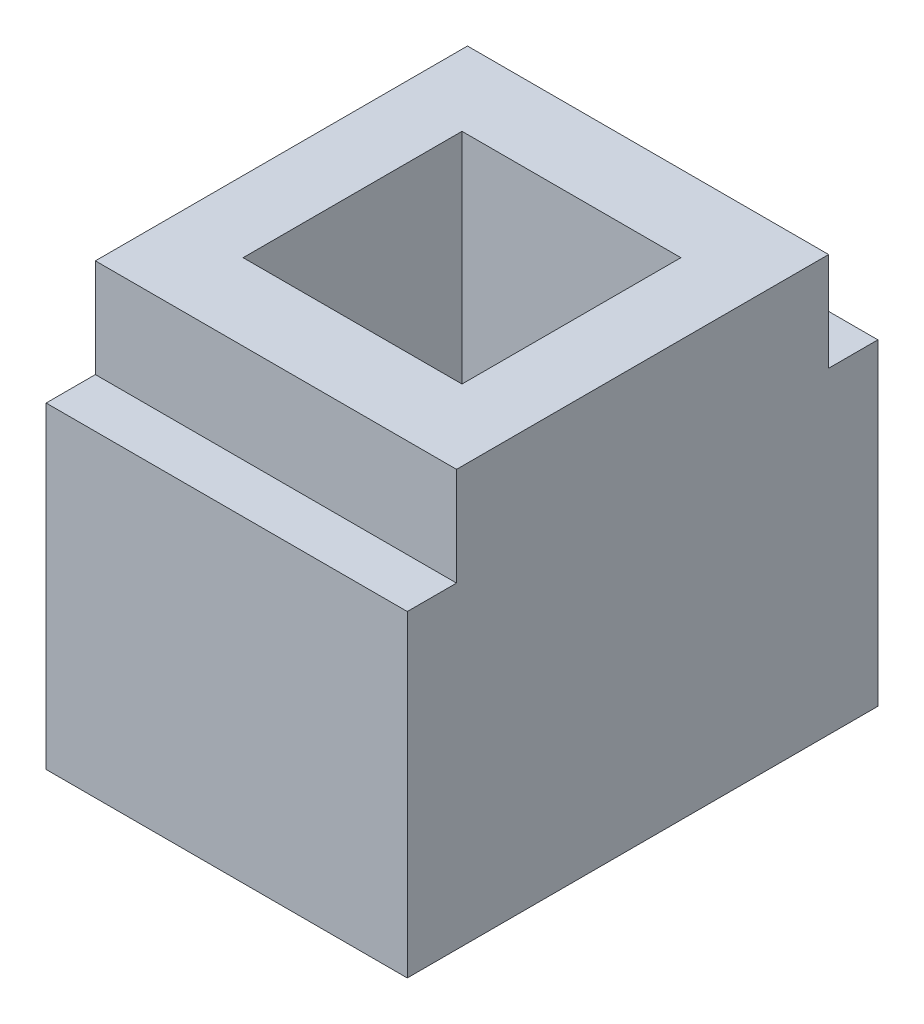
SolidWorks part; units mm, degrees
ref_plane "Alzado" through (0, 0, 0) normal (0, 0, 1) x (1, 0, 0)
ref_plane "Planta" through (0, 0, 0) normal (0, 1, 0) x (1, 0, 0)
ref_plane "Vista lateral" through (0, 0, 0) normal (1, 0, 0) x (0, 0, -1)
sketch "Croquis1" plane through (0, 0, 0) normal (1, 0, 0) x (0, 0, -1)
  line L0 (0, 0) -> (0, 31.7429) construction
  line L1 (-43, 38) -> (43, 38)
  line L2 (-43, 38) -> (-43, -38)
  line L3 (-43, -38) -> (43, -38)
  line L4 (43, 38) -> (43, -38)
  line L5 (-43, 38) -> (43, -38) construction
  line L6 (-43, -38) -> (43, 38) construction
  line L7 (-43, 38) -> (-34, 38)
  line L8 (-43, 38) -> (-43, 20)
  line L9 (-43, 20) -> (-34, 20)
  line L10 (-34, 38) -> (-34, 20)
  line L11 (43, 20) -> (34, 20)
  line L12 (34, 38) -> (34, 20)
  line L13 (43, 38) -> (34, 38)
  line L14 (43, 38) -> (43, 20)
  point P0 (0, 0)
  dimension "D1" = 86
  dimension "D2" = 76
  dimension "D3" = 58
  dimension "D4" = 68
extrude "Saliente-Extruir1" add sketch "Croquis1" along normal mid plane 66 contours L12 L1 L10 L9 L2 L3 L4 L11
sketch "Croquis2" plane through (0, 38, 0) normal (0, 1, 0) x (1, 0, 0)
  line L1 (-20, 20) -> (20, 20)
  line L2 (-20, 20) -> (-20, -20)
  line L3 (-20, -20) -> (20, -20)
  line L4 (20, 20) -> (20, -20)
  point P4 (20, 0)
  point P6 (0, 20)
  dimension "D1" = 40
  dimension "D2" = 40
extrude "Cortar-Extruir1" cut sketch "Croquis2" against normal through all
